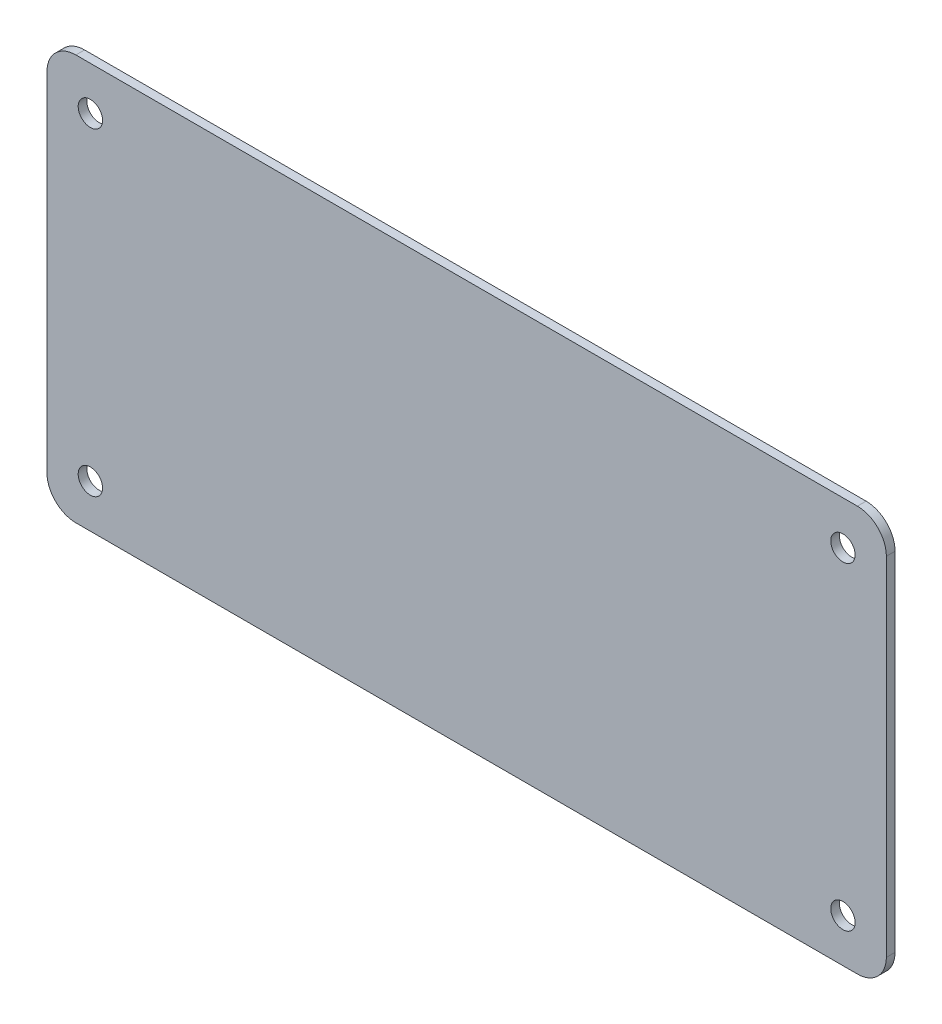
SolidWorks part; units mm, degrees
material "Q235"
ref_plane "前视基准面" through (0, 0, 0) normal (0, 0, 1) x (1, 0, 0)
ref_plane "上视基准面" through (0, 0, 0) normal (0, 1, 0) x (1, 0, 0)
ref_plane "右视基准面" through (0, 0, 0) normal (1, 0, 0) x (0, 0, -1)
sketch "草图1" plane through (0, 0, 0) normal (0, 0, 1) x (1, 0, 0)
  line L1 (-145, 70) -> (145, 70)
  line L2 (-145, 70) -> (-145, -70)
  line L3 (-145, -70) -> (145, -70)
  line L4 (145, 70) -> (145, -70)
  line L5 (-145, 70) -> (145, -70) construction
  line L6 (-145, -70) -> (145, 70) construction
  point P0 (0, 0)
  dimension "D1" = 290
  dimension "D2" = 140
extrude "凸台-拉伸1" add sketch "草图1" along normal blind 3
fillet "圆角1" radius 10 4 edges at (-145, 70, 1.5) (-145, -70, 1.5) (145, -70, 1.5) (145, 70, 1.5)
sketch "草图2" plane through (0, 0, 3) normal (0, 0, 1) x (1, 0, 0)
  line L0 (-145, 60) -> (-145, -60) construction
  line L1 (135, 70) -> (-135, 70) construction
  line L2 (-135, -70) -> (135, -70) construction
  line L3 (145, -60) -> (145, 60) construction
  circle A0 centre (-130, 55) radius 4.2136
  circle A1 centre (-130, -55) radius 4.2136
  circle A2 centre (130, 55) radius 4.2136
  circle A3 centre (130, -55) radius 4.2136
  dimension "D2" = 15
  dimension "D3" = 15
  dimension "D4" = 8.4273
  dimension "D5" = 15
  dimension "D6" = 15
  dimension "D7" = 15
  dimension "D8" = 15
  dimension "D9" = 15
  dimension "D1" = 15
extrude "切除-拉伸1" cut sketch "草图2" against normal blind 3
